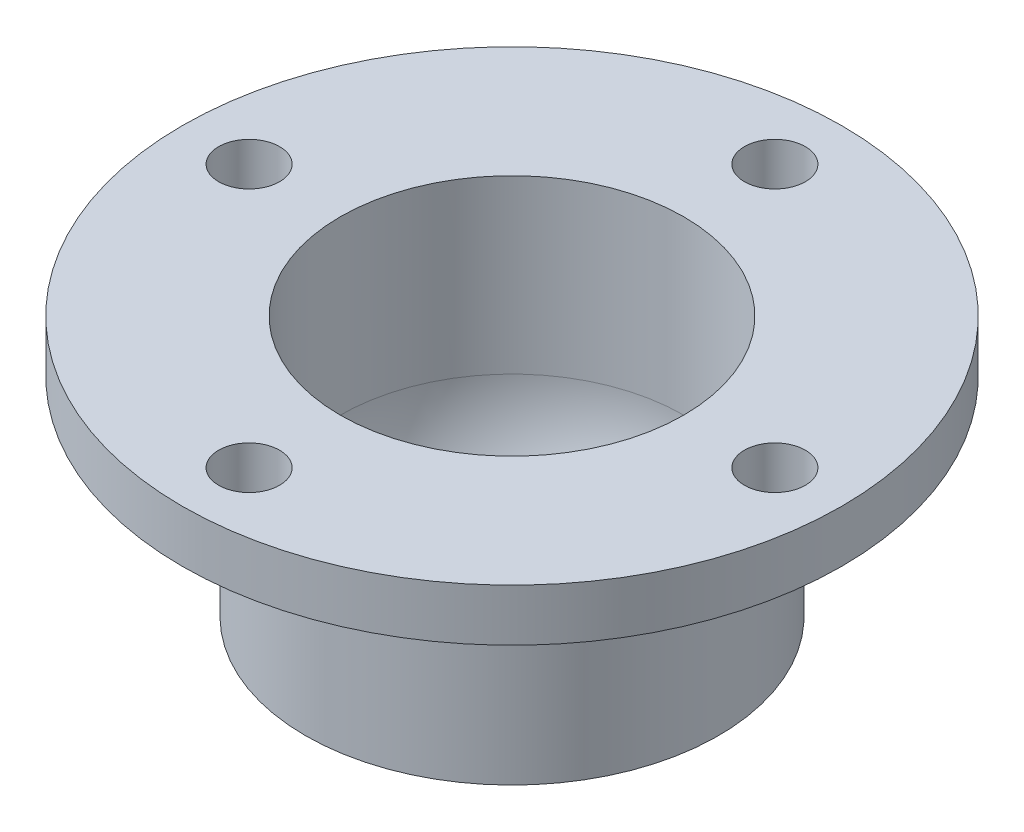
SolidWorks part; units mm, degrees
ref_plane "前视基准面" through (0, 0, 0) normal (0, 0, 1) x (1, 0, 0)
ref_plane "上视基准面" through (0, 0, 0) normal (0, 1, 0) x (1, 0, 0)
ref_plane "右视基准面" through (0, 0, 0) normal (1, 0, 0) x (0, 0, -1)
sketch "Sketch1" plane through (0, 0, 0) normal (0, 1, 0) x (1, 0, 0)
  circle A0 centre (0, 0) radius 11.9
  circle A1 centre (0, 0) radius 9.9
  dimension "D1" = 23.8
  dimension "D2" = 19.8
extrude "Boss-Extrude3" add sketch "Sketch1" along normal blind 15 contours A1 | A0
sketch "Sketch4" plane through (0, 0, 0) normal (0, -1, 0) x (1, 0, 0)
  circle A0 centre (0, 0) radius 9.9
extrude "Boss-Extrude4" add sketch "Sketch4" against normal blind 5.1
sketch "Sketch7" plane through (0, 0, 0) normal (1, 0, 0) x (0, 0, -1)
  line L0 (0, 15) -> (0, -4.8)
  arc A0 (0, -4.8) -> (0, 15) centre (0, 5.1) ccw
  dimension "D2" = 9.9
  dimension "D1" = 5.1
revolve "Cut-Revolve2" cut sketch "Sketch7" angle 360 about L0
sketch "Sketch12" plane through (0, 15, 0) normal (0, 1, 0) x (1, 0, 0)
  circle A0 centre (0, 0) radius 19
  circle A1 centre (0, 0) radius 11.9
  dimension "D1" = 38
extrude "Boss-Extrude8" add sketch "Sketch12" against normal blind 3
sketch "Sketch14" plane through (0, 15, 0) normal (0, 1, 0) x (1, 0, 0)
  line L0 (0, 0) -> (0, 22.9912) construction
  line L1 (0, 0) -> (27.8368, 0) construction
  line L2 (0, 0) -> (-27.3663, 0) construction
  line L3 (0, 0) -> (0, -24.0336) construction
  circle A0 centre (0, 15.15) radius 1.755
  circle A1 centre (-15.15, 0) radius 1.755
  circle A2 centre (0, -15.15) radius 1.755
  circle A3 centre (15.15, 0) radius 1.755
  dimension "D1" = 3.51
  dimension "D2" = 3.51
  dimension "D3" = 3.51
  dimension "D4" = 3.51
  dimension "D5" = 15.15
  dimension "D6" = 15.15
  dimension "D7" = 15.15
  dimension "D8" = 15.15
extrude "Cut-Extrude4" cut sketch "Sketch14" against normal blind 3
